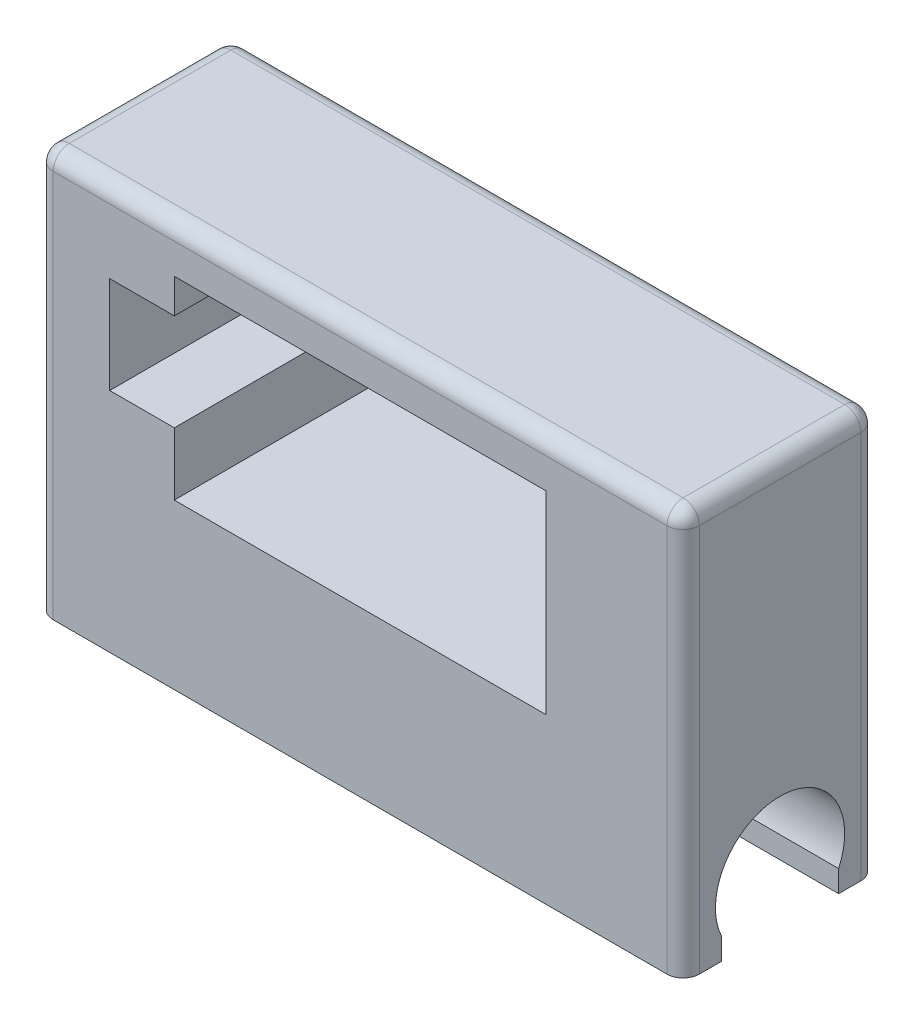
SolidWorks part; units mm, degrees
ref_plane "Front Plane" through (0, 0, 0) normal (0, 0, 1) x (1, 0, 0)
ref_plane "Top Plane" through (0, 0, 0) normal (0, 1, 0) x (1, 0, 0)
ref_plane "Right Plane" through (0, 0, 0) normal (1, 0, 0) x (0, 0, -1)
sketch "Sketch1" plane through (0, 0, 0) normal (1, 0, 0) x (0, 0, -1)
  line L2 (-3.625, -1.691) -> (-3.625, -3.0419)
  line L3 (-3.625, -3.0419) -> (-6, -3.0419)
  line L4 (-6, -3.0419) -> (-6, 6)
  line L5 (0, 55) -> (0, -55) construction
  line L6 (6, -3.0419) -> (6, 6)
  line L7 (3.625, -3.0419) -> (6, -3.0419)
  line L8 (3.625, -1.691) -> (3.625, -3.0419)
  line L10 (-6, 6) -> (6, 6)
  arc A0 (3.625, -1.691) -> (-3.625, -1.691) centre (0, 0) ccw
  point P12 (-6, 5.9151)
  dimension "D1" = 8
  dimension "D3" = 7.25
extrude "Boss-Extrude1" add sketch "Sketch1" along normal blind 40
sketch "Sketch2" plane through (0, 0, 6) normal (0, 0, 1) x (1, 0, 0)
  line L0 (8.5, 17) -> (8.5, 19.125)
  line L1 (0, 6) -> (40, 6)
  line L2 (0, 6) -> (0, 22)
  line L3 (0, 22) -> (40, 22)
  line L4 (40, 6) -> (40, 22)
  line L5 (8.5, 7.125) -> (31.5, 7.125)
  line L6 (8.5, 7.125) -> (8.5, 11)
  line L7 (8.5, 19.125) -> (31.5, 19.125)
  line L8 (31.5, 7.125) -> (31.5, 19.125)
  line L9 (8.5, 11) -> (4.5, 11)
  line L11 (8.5, 17) -> (4.5, 17)
  line L12 (4.5, 11) -> (4.5, 17)
  point P5 (20, 7.125)
  point P11 (20, 6)
  point P12 (0, 0)
  point P13 (0, 14)
  point P18 (4.5, 14)
  point P19 (0, 0)
  dimension "D1" = 12
  dimension "D2" = 23
  dimension "D3" = 16
  dimension "D4" = 6
  dimension "D5" = 4
extrude "Boss-Extrude2" add sketch "Sketch2" against normal up to surface (12 mm away) up to face at (20, 1.4791, -6)
fillet "Fillet1" radius 1 8 edges at (40, 22, 0) (20, 22, 6) (0, 22, 0) (20, 22, -6) (0, 9.4791, 6) (40, 9.4791, 6) (0, 9.4791, -6) (40, 9.4791, -6)
